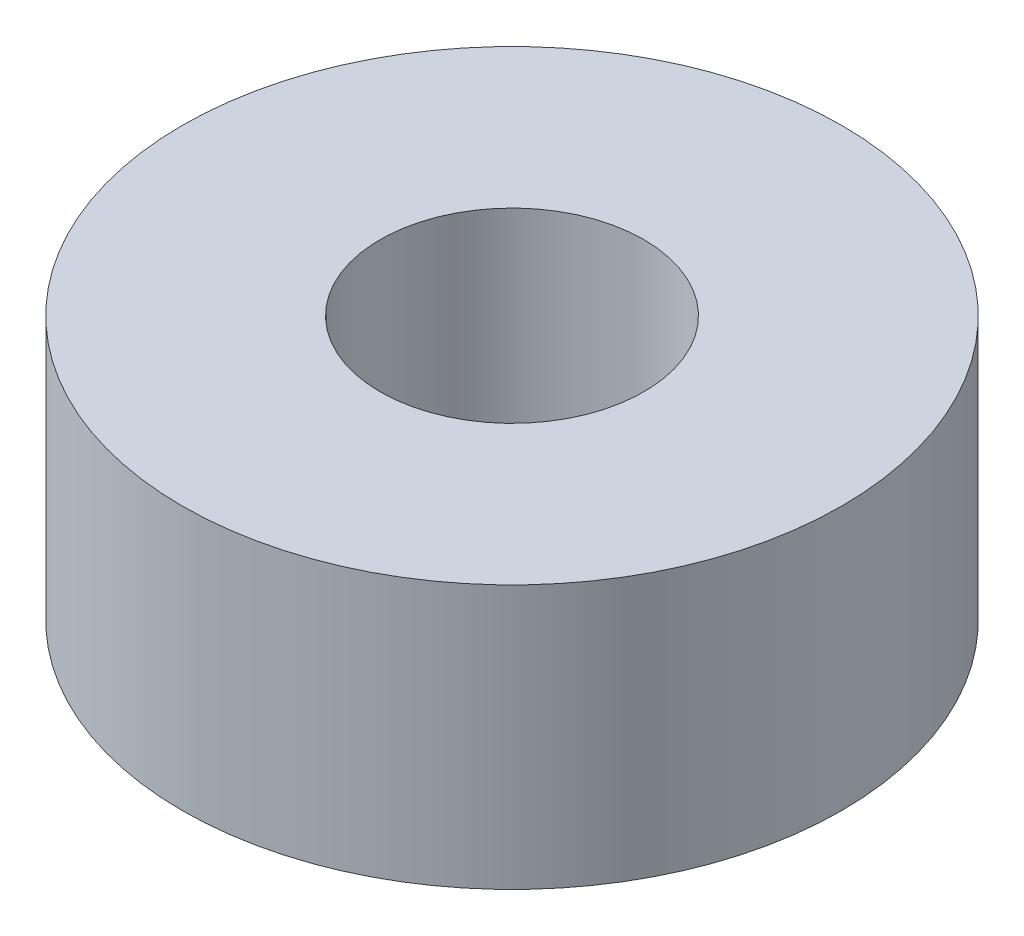
SolidWorks part; units mm, degrees
material "Plain Carbon Steel"
ref_plane "Front Plane" through (0, 0, 0) normal (0, 0, 1) x (1, 0, 0)
ref_plane "Top Plane" through (0, 0, 0) normal (0, 1, 0) x (1, 0, 0)
ref_plane "Right Plane" through (0, 0, 0) normal (1, 0, 0) x (0, 0, -1)
sketch "Sketch1" plane through (0, 0, 0) normal (0, 1, 0) x (1, 0, 0)
  circle A0 centre (0, 0) radius 5
  circle A1 centre (0, 0) radius 2
  dimension "D1" = 10
  dimension "D2" = 4
extrude "Boss-Extrude1" add sketch "Sketch1" along normal blind 4
